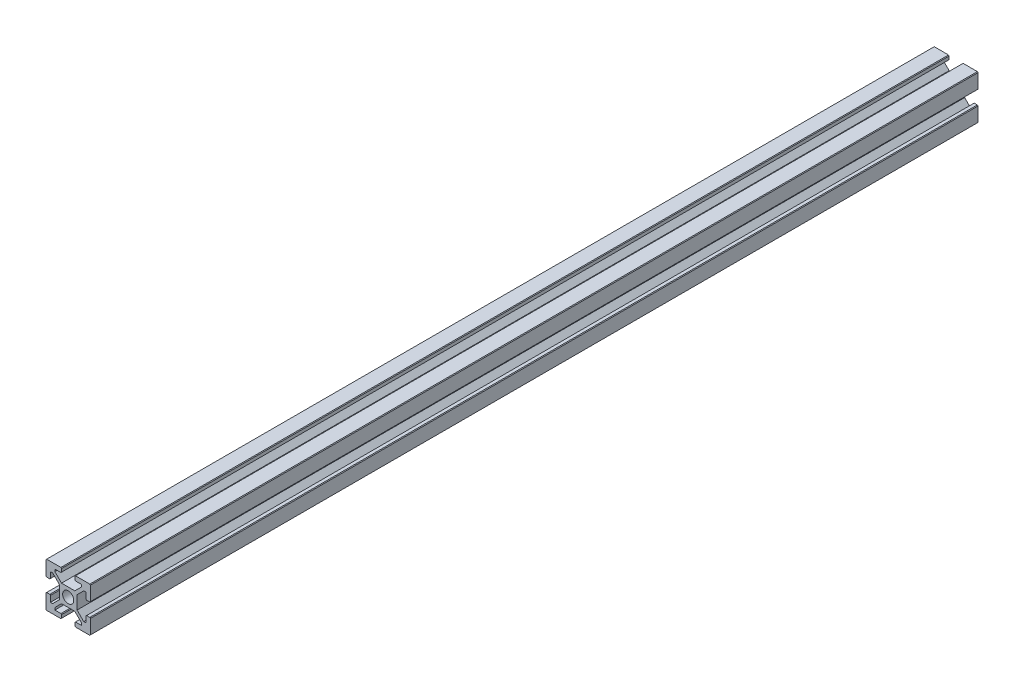
SolidWorks part; units mm, degrees
ref_plane "Front" through (0, 0, 0) normal (0, 0, 1) x (1, 0, 0)
ref_plane "Top" through (0, 0, 0) normal (0, 1, 0) x (1, 0, 0)
ref_plane "Right" through (0, 0, 0) normal (1, 0, 0) x (0, 0, -1)
sketch "Sketch1" plane through (0, 0, 0) normal (0, 0, 1) x (1, 0, 0)
  line L0 (-3, 10) -> (3, 10)
  line L1 (-10, 10) -> (10, 10)
  line L2 (-10, 10) -> (-10, -10)
  line L3 (-10, -10) -> (10, -10)
  line L4 (10, 10) -> (10, -10)
  line L5 (-10, 10) -> (10, -10) construction
  line L6 (-10, -10) -> (10, 10) construction
  line L7 (3, 10) -> (3, 8)
  line L8 (3, 8) -> (6, 8)
  line L9 (-3, 4) -> (3, 4)
  line L10 (0, -55) -> (0, 55) construction
  line L11 (3, 4) -> (6, 7)
  line L12 (6, 7) -> (6, 8)
  line L13 (10, 3) -> (10, -3)
  line L14 (-3, 10) -> (-3, 8)
  line L15 (-3, 8) -> (-6, 8)
  line L16 (-6, 7) -> (-6, 8)
  line L17 (-3, 4) -> (-6, 7)
  line L18 (10, -3) -> (8, -3)
  line L19 (8, -3) -> (8, -6)
  line L20 (7, -6) -> (8, -6)
  line L21 (4, -3) -> (7, -6)
  line L22 (4, 3) -> (4, -3)
  line L23 (4, 3) -> (7, 6)
  line L24 (7, 6) -> (8, 6)
  line L25 (8, 3) -> (8, 6)
  line L26 (10, 3) -> (8, 3)
  line L27 (3, -10) -> (-3, -10)
  line L28 (-3, -10) -> (-3, -8)
  line L29 (-3, -8) -> (-6, -8)
  line L30 (-6, -7) -> (-6, -8)
  line L31 (-3, -4) -> (-6, -7)
  line L32 (3, -4) -> (-3, -4)
  line L33 (3, -4) -> (6, -7)
  line L34 (6, -7) -> (6, -8)
  line L35 (3, -8) -> (6, -8)
  line L36 (3, -10) -> (3, -8)
  line L37 (-10, -3) -> (-10, 3)
  line L38 (-10, 3) -> (-8, 3)
  line L39 (-8, 3) -> (-8, 6)
  line L40 (-7, 6) -> (-8, 6)
  line L41 (-4, 3) -> (-7, 6)
  line L42 (-4, -3) -> (-4, 3)
  line L43 (-4, -3) -> (-7, -6)
  line L44 (-7, -6) -> (-8, -6)
  line L45 (-8, -3) -> (-8, -6)
  line L46 (-10, -3) -> (-8, -3)
  circle A0 centre (0, 0) radius 2.5
  point P0 (0, 0)
  point P18 (0, 10)
  point P22 (0, 4)
  point P53 (0, 0)
  dimension "D9" = 5
  dimension "D1" = 20
  dimension "D2" = 20
  dimension "D3" = 3
  dimension "D4" = 2
  dimension "D5" = 3
  dimension "D6" = 6
  dimension "D7" = 3
  dimension "D8" = 4
extrude "Boss-Extrude1" add sketch "Sketch1" along normal blind 400 contours L46 L2 L3 L28 L29 L30 L31 L32 L33 L34 L35 L36 L4 L18 L19 L20 L21 L22 L23 L24 L25 L26 L1 L7 L8 L12 L11 L9 L17 L16 L15 L14 L38 L39 L40 L41 L42 L43 L44 L45 A0
chamfer "Chamfer1" distance 0.2828 angle 45 20 edges at (-8, 3, 200) (-3, 8, 200) (-3, 10, 200) (-10, 3, 200) (-10, 10, 200) (-8, -3, 200) (-10, -3, 200) (-10, -10, 200) (-3, -10, 200) (-3, -8, 200) (3, -8, 200) (3, -10, 200) (8, -3, 200) (10, -10, 200) (10, -3, 200) (8, 3, 200) (10, 3, 200) (10, 10, 200) (3, 8, 200) (3, 10, 200)
